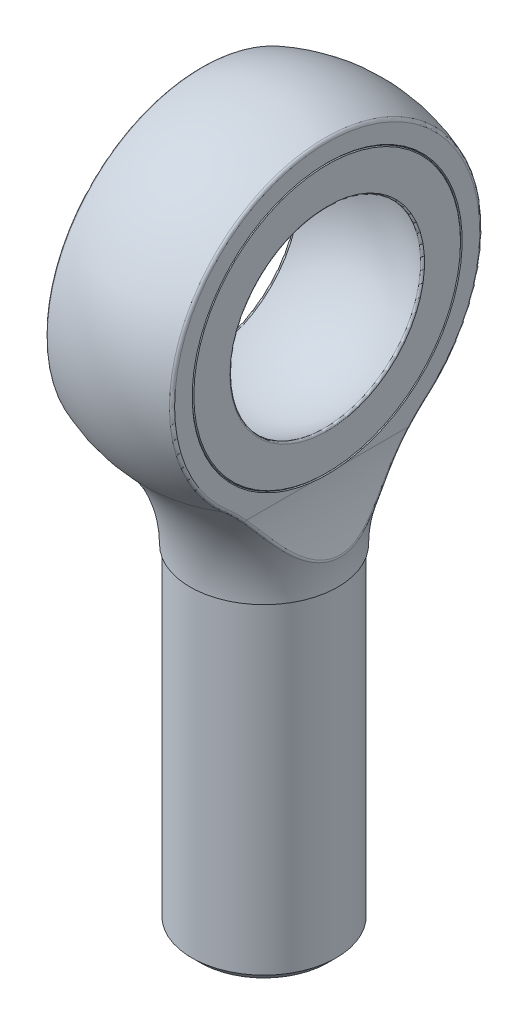
SolidWorks part; units mm, degrees
material "AISI 4340 Steel, normalized"
ref_plane "Front Plane" through (0, 0, 0) normal (0, 0, 1) x (1, 0, 0)
ref_plane "Top Plane" through (0, 0, 0) normal (0, 1, 0) x (1, 0, 0)
ref_plane "Right Plane" through (0, 0, 0) normal (1, 0, 0) x (0, 0, -1)
sketch "Sketch1" plane through (0, 0, 0) normal (0, 0, 1) x (1, 0, 0)
  line L0 (0, 0) -> (9.7155, 0) construction
  line L1 (0, 20.6375) -> (9.7155, 20.6375)
  line L2 (9.7155, 20.6375) -> (9.7155, 14.5103)
  line L3 (0, 20.6375) -> (0, 17.4625)
  line L4 (0, 0) -> (0, 17.4625) construction
  arc A0 (9.7155, 14.5103) -> (0, 17.4625) centre (0, 0) ccw
  dimension "Ball_Dia" = 34.925
  dimension "S" = 41.275
  dimension "H" = 19.431
revolve "Revolve1" add sketch "Sketch1" angle 360 about L0
chamfer "Chamfer1" distance 0.127 angle 45 1 edges at (9.7155, 0, 20.6375)
fillet "Fillet1" radius 0.254 1 edges at (9.7155, 0, 14.5103)
mirror "Mirror1" about plane through (0, 0, 0) normal (1, 0, 0) of bodies 101
sketch "Sketch2" plane through (0, 0, 0) normal (0, 0, 1) x (1, 0, 0)
  line L0 (0, 0) -> (0, 32.415) construction
  line L1 (0, 25.7175) -> (0, -85.725)
  line L2 (0, -85.725) -> (11.1125, -85.725)
  line L4 (11.3665, -34.925) -> (11.1125, -34.925)
  line L5 (11.1125, -34.925) -> (11.1125, -85.725)
  arc A0 (11.3665, -34.925) -> (18.2874, -18.082) centre (35.3217, -34.925) cw
  arc A1 (18.2874, -18.082) -> (0, 25.7175) centre (0, 0) ccw
  dimension "D" = 51.435
  dimension "D2" = 0.254
  dimension "A" = 85.725
  dimension "Thread_Dia" = 22.225
  dimension "C" = 50.8
revolve "Revolve2" add sketch "Sketch2" angle 360 about L0
sketch "Sketch3" plane through (0, 0, 0) normal (0, 0, 1) x (1, 0, 0)
  line L0 (9.7155, 55.5625) -> (9.7155, -20.6375)
  line L1 (9.7155, -20.5105) -> (9.7155, 20.5105) construction
  line L2 (-9.5885, -20.6375) -> (9.5885, -20.6375) construction
  arc A0 (9.7155, -20.6375) -> (35.1155, -46.0375) centre (35.1155, -20.6375) ccw
  dimension "D1" = 25.4
  dimension "D2" = 76.2
extrude "Cut-Extrude1" cut sketch "Sketch3" against normal through all and the other way through all
mirror "Mirror2" about plane through (0, 0, 0) normal (1, 0, 0) of "Cut-Extrude1"
sketch "Sketch4" plane through (0, 0, 0) normal (1, 0, 0) x (0, 0, -1)
  circle A0 centre (0, 0) radius 20.6375 construction
  circle A1 centre (0, 0) radius 20.6375
extrude "Cut-Extrude2" cut sketch "Sketch4" against normal through all both and the other way through all
chamfer "Chamfer2" distance 0.127 angle 45 1 edges at (9.7155, 20.6375, 0)
chamfer "Chamfer3" distance 1.27 angle 45 1 edges at (0, -85.725, -11.1125)
fillet "Fillet2" radius 0.508 8 edges at (-9.7155, -54.3043, -48.4388) (-11.7338, -30.5599, -0.8909) (9.7155, -54.3043, -48.4388) (11.7338, -30.5599, -0.8909) (-9.7155, 23.8117, 0) (9.7155, 23.8117, 0)
